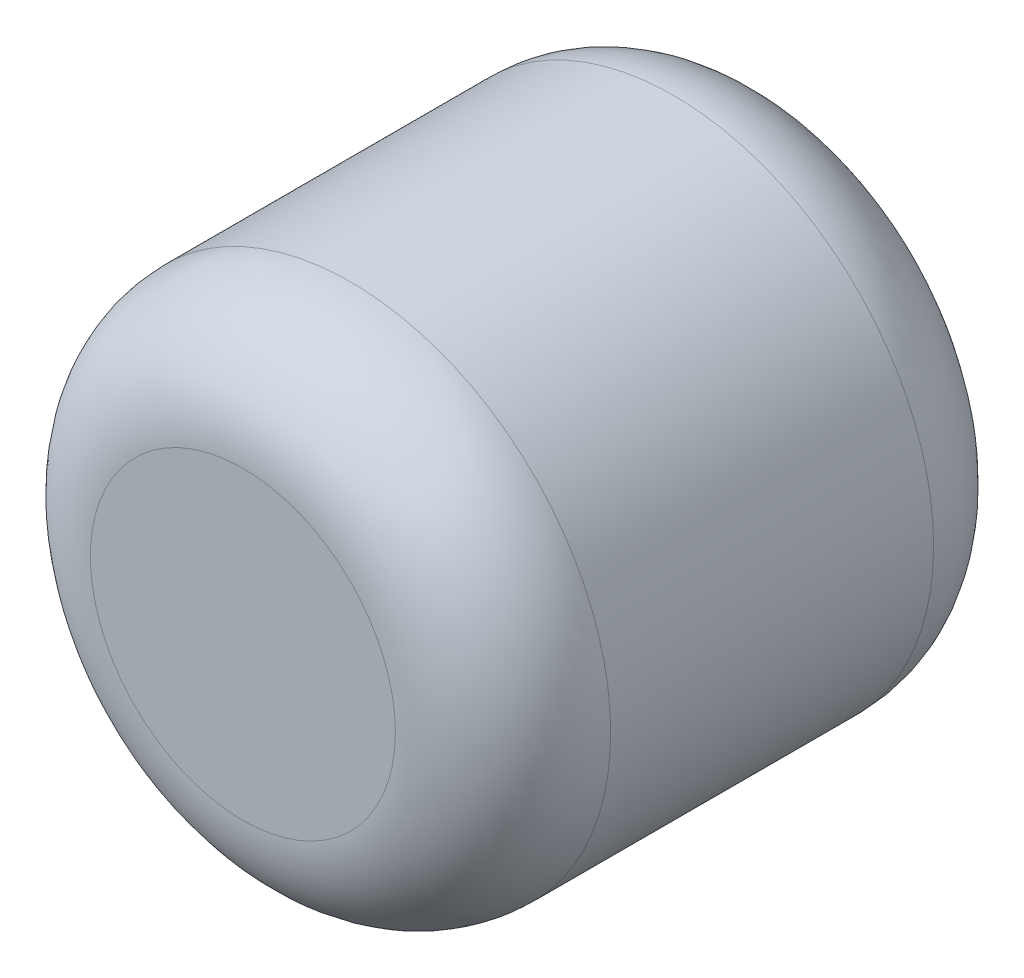
SolidWorks part; units mm, degrees
ref_plane "Front Plane" through (0, 0, 0) normal (0, 0, 1) x (1, 0, 0)
ref_plane "Top Plane" through (0, 0, 0) normal (0, 1, 0) x (1, 0, 0)
ref_plane "Right Plane" through (0, 0, 0) normal (1, 0, 0) x (0, 0, -1)
sketch "Sketch2" plane through (0, 0, 0) normal (0, 0, 1) x (1, 0, 0)
  circle A0 centre (0, 0) radius 7.25
  dimension "D1" = 14.5
extrude "Boss-Extrude1" add sketch "Sketch2" along normal blind 15
ref_point "Point1"
ref_point "Point2"
fillet "Fillet1" radius 3 2 edges at (7.25, 0, 15) (7.25, 0, 0)
